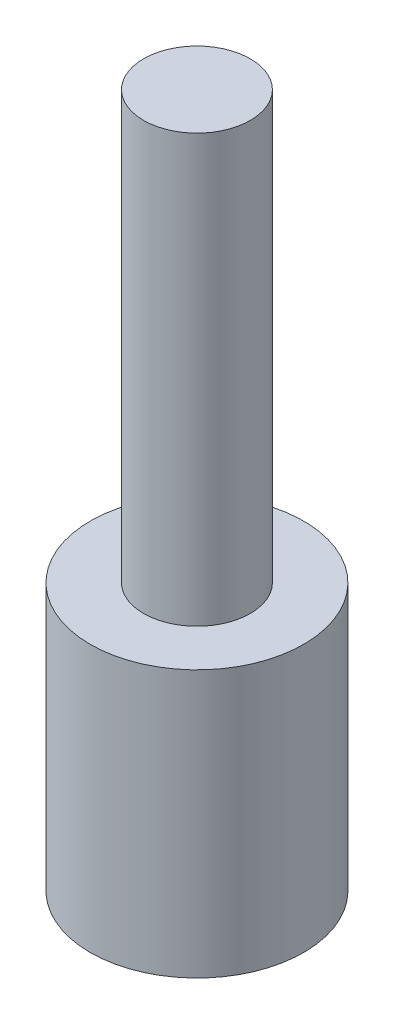
SolidWorks part; units mm, degrees
ref_plane "Front Plane" through (0, 0, 0) normal (0, 0, 1) x (1, 0, 0)
ref_plane "Top Plane" through (0, 0, 0) normal (0, 1, 0) x (1, 0, 0)
ref_plane "Right Plane" through (0, 0, 0) normal (1, 0, 0) x (0, 0, -1)
sketch "Sketch1" plane through (0, 0, 0) normal (0, 1, 0) x (1, 0, 0)
  circle A0 centre (0, 0) radius 20
extrude "Boss-Extrude1" add sketch "Sketch1" along normal blind 50
sketch "Sketch2" plane through (0, 50, 0) normal (0, 1, 0) x (1, 0, 0)
  circle A0 centre (0, 0) radius 10
extrude "Boss-Extrude2" add sketch "Sketch2" along normal blind 80
